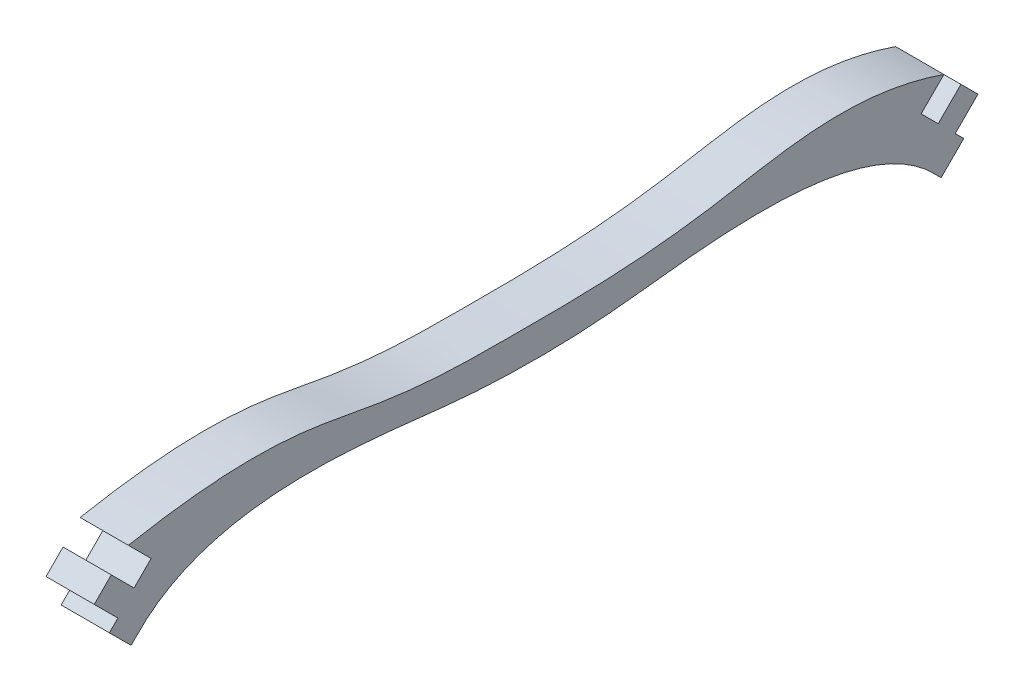
SolidWorks part; units mm, degrees
ref_plane "Piano frontale" through (0, 0, 0) normal (0, 0, 1) x (1, 0, 0)
ref_plane "Piano superiore" through (0, 0, 0) normal (0, 1, 0) x (1, 0, 0)
ref_plane "Piano destro" through (0, 0, 0) normal (1, 0, 0) x (0, 0, -1)
sketch "Schizzo1" plane through (0, 0, 0) normal (1, 0, 0) x (0, 0, -1)
  line L0 (-54.9497, -4.9497) -> (-52.8284, -2.8284)
  line L1 (-52.8284, -2.8284) -> (-50, -5.6569)
  line L2 (-50, -5.6569) -> (-47.8787, -3.5355)
  line L3 (-47.8787, -3.5355) -> (-50.7071, -0.7071)
  line L4 (-50.7071, -0.7071) -> (-50, 0)
  line L6 (-50, 0) -> (50, 0)
  line L8 (50, 0) -> (50.7071, -0.7071)
  line L9 (50.7071, -0.7071) -> (47.8787, -3.5355)
  line L10 (47.8787, -3.5355) -> (50, -5.6569)
  line L11 (50, -5.6569) -> (52.8284, -2.8284)
  line L12 (52.8284, -2.8284) -> (54.9497, -4.9497)
  line L14 (49.6575, -10.9491) -> (-49.6575, -10.9491)
  line L16 (-54.9497, -4.9497) -> (-52.0078, -7.8917)
  line L17 (-52.0078, -7.8917) -> (-53.0685, -8.9524)
  line L18 (-53.0685, -8.9524) -> (-50.3646, -11.6562)
  line L19 (-50.3646, -11.6562) -> (-49.6575, -10.9491)
  line L20 (54.9497, -4.9497) -> (52.1213, -7.7782)
  line L21 (52.1213, -7.7782) -> (53.182, -8.8388)
  line L22 (53.182, -8.8388) -> (50.3646, -11.6562)
  line L23 (50.3646, -11.6562) -> (49.6575, -10.9491)
  line L24 (119.4315, 16.6508) -> (-69.3003, -16.6277) construction
  line L25 (78.1229, -18.1833) -> (-127.8189, 18.1298) construction
  line L26 (82.1883, -2) -> (-82.1851, -2) construction
  line L27 (79.6028, -13.2141) -> (-119.6361, 4.217) construction
  line L28 (119.6395, 4.2173) -> (-79.5994, -13.2138) construction
  line L29 (126.8915, -6) -> (-126.8916, -6) construction
  spline S0 degree 3 poles (-49.6575, -10.9491) (-42.2979, -3.2139) (-21.5917, -3.8505) (-7.8109, -6.0082) (7.8109, -6.0082) (21.5917, -3.8505) (42.2979, -3.2139) (49.6575, -10.9491) knots 0 0 0 0 0.322683 0.480298 0.519702 0.677317 1 1 1 1
  spline S1 degree 3 poles (-50.7071, -0.7071) (-34.9409, 2.2763) (-17.5881, -2.0063) (-8.1505, -1.9737) (7.0397, -2.0279) (22.7757, -1.2144) (39.3055, 3.2539) (50.7071, -0.7071) knots 0 0 0 0 0.188415 0.445999 0.506836 0.735949 1 1 1 1
  point P18 (0, 0)
  dimension "D19" = 25
  dimension "D18" = 50
  dimension "D25" = 50
  dimension "D28" = 50
  dimension "D31" = 50
  dimension "D32" = 50
  dimension "D33" = 50
  dimension "D1" = 3
  dimension "D2" = 45
  dimension "D3" = 3
  dimension "D4" = 1
  dimension "D5" = 1
  dimension "D6" = 3
  dimension "D7" = 3
  dimension "D8" = 20
  dimension "D9" = 20
  dimension "D10" = 100
  dimension "D11" = 135
  dimension "D12" = 8
  dimension "D13" = 4
  dimension "D14" = 4
  dimension "D15" = 4
  dimension "D16" = 4
  dimension "D17" = 4
  dimension "D20" = 25
  dimension "D21" = 1
  dimension "D22" = 1.5
  dimension "D23" = 1.5
  dimension "D24" = 1
  dimension "D26" = 170
  dimension "D27" = 190
  dimension "D29" = 135
  dimension "D30" = 1.5
  dimension "D34" = 5
  dimension "D35" = 5
  dimension "D36" = 135
  dimension "D37" = 6
  dimension "D38" = 2
extrude "Estrusione-Estrusione1" add sketch "Schizzo1" along normal blind 6
